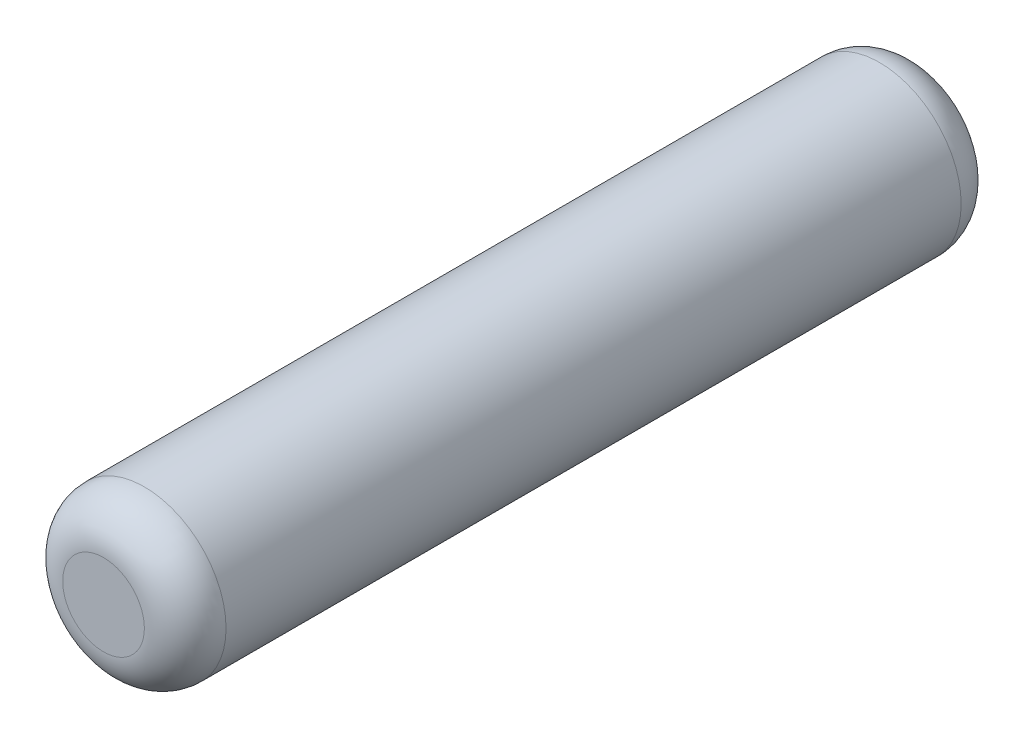
SolidWorks part; units mm, degrees
ref_plane "Plane1" through (0, 0, 0) normal (0, 0, 1) x (1, 0, 0)
ref_plane "plan de coupe 1" through (0, 0, 0) normal (0, 1, 0) x (1, 0, 0)
ref_plane "Plane3" through (0, 0, 0) normal (1, 0, 0) x (0, 0, -1)
sketch "Esquisse1" plane through (0, 0, 0) normal (0, 0, 1) x (1, 0, 0)
  circle A0 centre (0, 0) radius 2
  dimension "D1" = 4
extrude "axe" add sketch "Esquisse1" along normal blind 20
fillet "Cong" radius 1
ref_plane "plan de coupe 2" through (0, 0, 10) normal (0, 0, 1) x (1, 0, 0)
